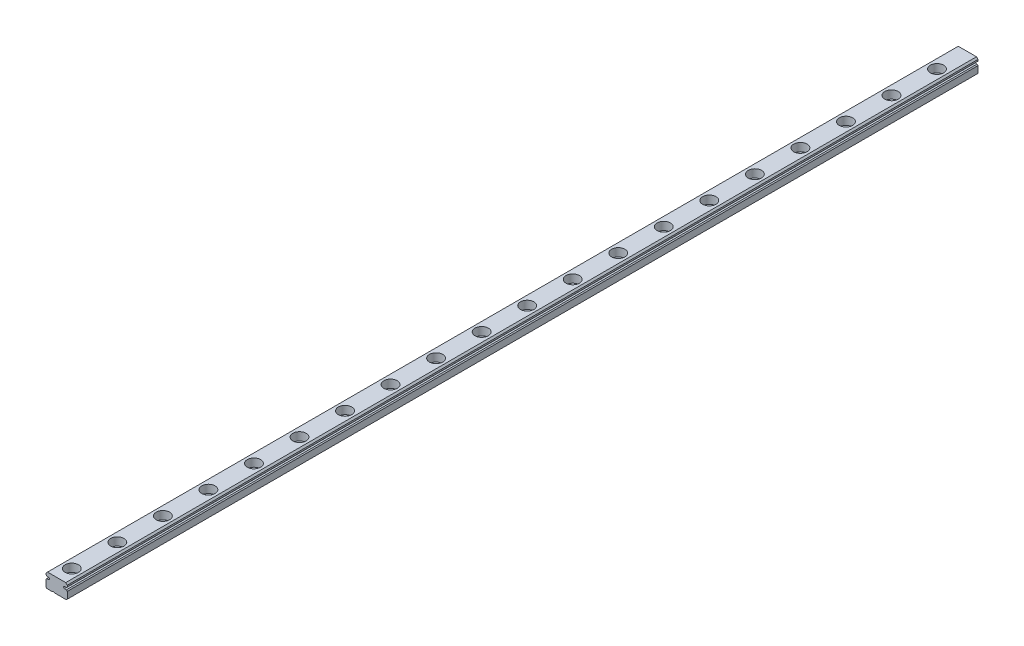
SolidWorks part; units mm, degrees
ref_plane "Front Plane" through (0, 0, 0) normal (0, 0, 1) x (1, 0, 0)
ref_plane "Top Plane" through (0, 0, 0) normal (0, 1, 0) x (1, 0, 0)
ref_plane "Right Plane" through (0, 0, 0) normal (1, 0, 0) x (0, 0, -1)
sketch "Sketch3" plane through (0, 0, 0) normal (0, 0, 1) x (1, 0, 0)
  line L0 (-3.5, 0) -> (-1.35, 0)
  line L1 (0, 0) -> (0, 4.8) construction
  line L2 (-3.5, 4.8) -> (3.5, 4.8)
  line L3 (-3.5, 0) -> (-3.5, 2.83)
  line L4 (3.5, 4.8) -> (3.5, 3.5)
  line L5 (-3.5, 3.5) -> (-2.65, 3.5)
  line L6 (-2.65, 3.5) -> (-2.65, 2.83) construction
  line L7 (-2.65, 2.83) -> (-3.5, 2.83)
  line L8 (-3.5, 3.5) -> (-3.5, 4.8)
  line L9 (2.65, 3.5) -> (2.65, 2.83) construction
  line L10 (2.65, 2.83) -> (3.5, 2.83)
  line L11 (3.5, 3.5) -> (2.65, 3.5)
  line L12 (3.5, 2.83) -> (3.5, 0)
  line L13 (-0.65, 0) -> (3.5, 0)
  arc A0 (-2.65, 3.5) -> (-2.65, 2.83) centre (-2.65, 3.165) cw
  arc A1 (2.65, 3.5) -> (2.65, 2.83) centre (2.65, 3.165) ccw
  arc A2 (-1.35, 0) -> (-0.65, 0) centre (-1, -0.3571) cw
  point P8 (0, 4.8)
  dimension "D8" = 0.5
  dimension "D1" = 7
  dimension "D2" = 4.8
  dimension "D3" = 1.3
  dimension "D4" = 2.65
  dimension "D5" = 0.67
  dimension "D6" = 1
  dimension "D7" = 0.7
extrude "Boss-Extrude1" add sketch "Sketch3" along normal mid plane 300
chamfer "Chamfer1" distance 0.5 angle 45 2 edges at (3.5, 4.8, 0) (-3.5, 4.8, 0)
chamfer "Chamfer2" distance 0.3 angle 45 6 edges at (3.5, 0, 0) (-3.5, 0, 0) (-3.5, 2.83, 0) (3.5, 2.83, 0) (3.5, 3.5, 0) (-3.5, 3.5, 0)
hole_wizard "CBORE for M2 SHCS1" positions "Sketch4" profile "Sketch5" counterbore size "M2" standard "ANSI Metric" end condition up to next
sketch "Sketch4" plane through (0, 4.8, 0) normal (0, 1, 0) x (1, 0, 0)
  line L0 (3, -150) -> (-3, -150) construction
  point P0 (0, -145)
  dimension "D1" = 5
sketch "Sketch5" plane through (0, 4.8, 145) normal (1, 0, 0) x (0, 0, 1)
  line L0 (0, 0) -> (0, 4.8)
  line L1 (0, 4.8) -> (1.2, 4.8)
  line L3 (1.2, 4.8) -> (1.2, 2.65)
  line L4 (1.2, 2.65) -> (2.2, 2.65)
  line L5 (2.2, 2.65) -> (2.2, 0)
  line L7 (2.2, 0) -> (0, 0)
  line L11 (0, -6.35) -> (0, 107.95) construction
  dimension "Thru Hole Dia." = 2.4
  dimension "Thru Hole Depth" = 4.8
  dimension "C'Bore Dia." = 4.4
  dimension "C'Bore Depth" = 2.65
pattern_linear "LPattern1" count 20 spacing 15 along (0, 0, -1) of "CBORE for M2 SHCS1"
